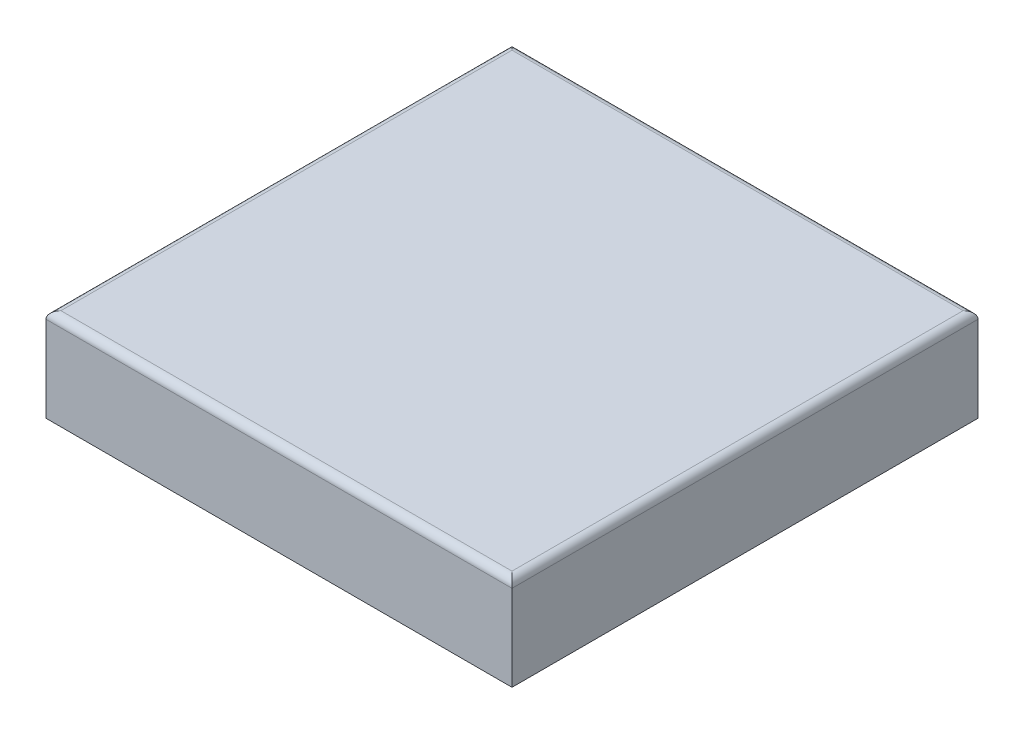
SolidWorks part; units mm, degrees
ref_plane "Front" through (0, 0, 0) normal (0, 0, 1) x (1, 0, 0)
ref_plane "Top" through (0, 0, 0) normal (0, 1, 0) x (1, 0, 0)
ref_plane "Right" through (0, 0, 0) normal (1, 0, 0) x (0, 0, -1)
sketch "Sketch1" plane through (0, 0, 0) normal (0, 1, 0) x (1, 0, 0)
  line L0 (0, 0) -> (0, 50.4571) construction
  line L1 (0, 0) -> (55.8847, 0) construction
  line L2 (-7.9375, 7.9375) -> (7.9375, 7.9375)
  line L3 (-7.9375, 7.9375) -> (-7.9375, -7.9375)
  line L4 (7.9375, -7.9375) -> (-7.9375, -7.9375)
  line L5 (7.9375, -7.9375) -> (7.9375, 7.9375)
  dimension "Length" = 15.875
  dimension "Width" = 15.875
extrude "Base-Extrude" add sketch "Sketch1" along normal blind 3.175
shell "Shell1" thickness 1.5875
sketch "Sketch4" plane through (0, 1.5875, 0) normal (0, -1, 0) x (1, 0, 0)
  circle A0 centre (-3.81, 0) radius 1.27
  circle A1 centre (0, 3.81) radius 1.27
  dimension "D1" = 2.54
extrude "Boss-Extrude2" add sketch "Sketch4" along normal up to surface (1.5875 mm away)
sketch "Sketch5" plane through (0, 0, 0) normal (0, -1, 0) x (1, 0, 0)
  circle A0 centre (0, 3.81) radius 0.635
  circle A1 centre (-3.81, 0) radius 0.635
  dimension "D1" = 1.27
extrude "Cut-Extrude2" cut sketch "Sketch5" against normal up to surface (1.5875 mm away)
fillet "Fillet1" radius 0.254 4 edges at (7.9375, 3.175, 0) (0, 3.175, -7.9375) (-7.9375, 3.175, 0) (0, 3.175, 7.9375)
sketch "Sketch7" plane through (0, 1.5875, 0) normal (0, -1, 0) x (1, 0, 0)
  line L0 (-6.35, 6.35) -> (6.35, -6.35) construction
sketch "Sketch8" plane through (0, 1.5875, 0) normal (0, -1, 0) x (1, 0, 0)
  line L0 (6.35, 6.35) -> (-6.35, -6.35) construction
